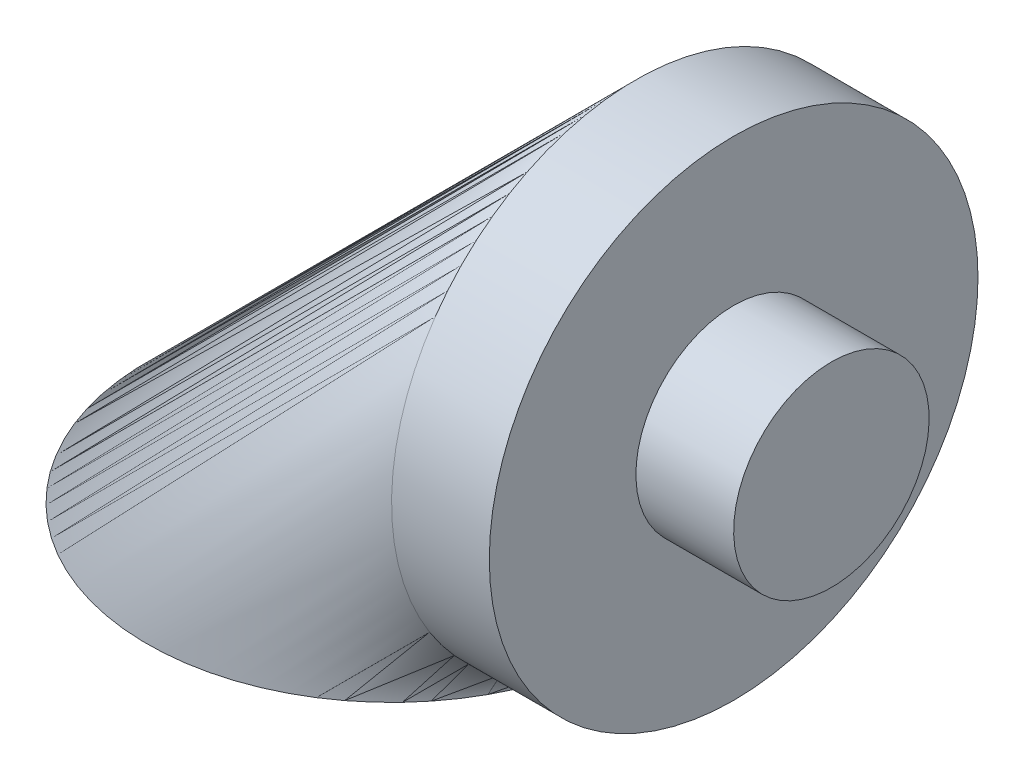
SolidWorks part; units mm, degrees
ref_plane "Front Plane" through (0, 0, 0) normal (0, 0, 1) x (1, 0, 0)
ref_plane "Top Plane" through (0, 0, 0) normal (0, 1, 0) x (1, 0, 0)
ref_plane "Right Plane" through (0, 0, 0) normal (1, 0, 0) x (0, 0, -1)
sketch "Sketch1" plane through (0, 0, 0) normal (0, 1, 0) x (1, 0, 0)
  circle A0 centre (0, 0) radius 50
sketch "Sketch2" plane through (0, 0, 0) normal (0, 0, 1) x (1, 0, 0)
  line L0 (50, 0) -> (-50, 0) construction
  arc A0 (50, 50) -> (0, 0) centre (50, 0) ccw
sweep "Sweep1" add profiles "Sketch1" path "Sketch2"
sketch "Sketch4" plane through (0, 0, 0) normal (0, -1, 0) x (1, 0, 0)
  circle A0 centre (0, 0) radius 20
extrude "Boss-Extrude2" add sketch "Sketch4" along normal blind 20
sketch "Sketch5" plane through (50, 0, 0) normal (1, 0, 0) x (0, 0, -1)
  line L0 (0, 50) -> (0, 0) construction
  line L1 (0, 55) -> (0, -55) construction
  circle A0 centre (0, 50) radius 50
extrude "Boss-Extrude3" add sketch "Sketch5" along normal blind 20
sketch "Sketch6" plane through (70, 0, 0) normal (1, 0, 0) x (0, 0, -1)
  line L0 (0, 50) -> (0, 0) construction
  circle A0 centre (0, 50) radius 20
extrude "Boss-Extrude4" add sketch "Sketch6" along normal blind 20
